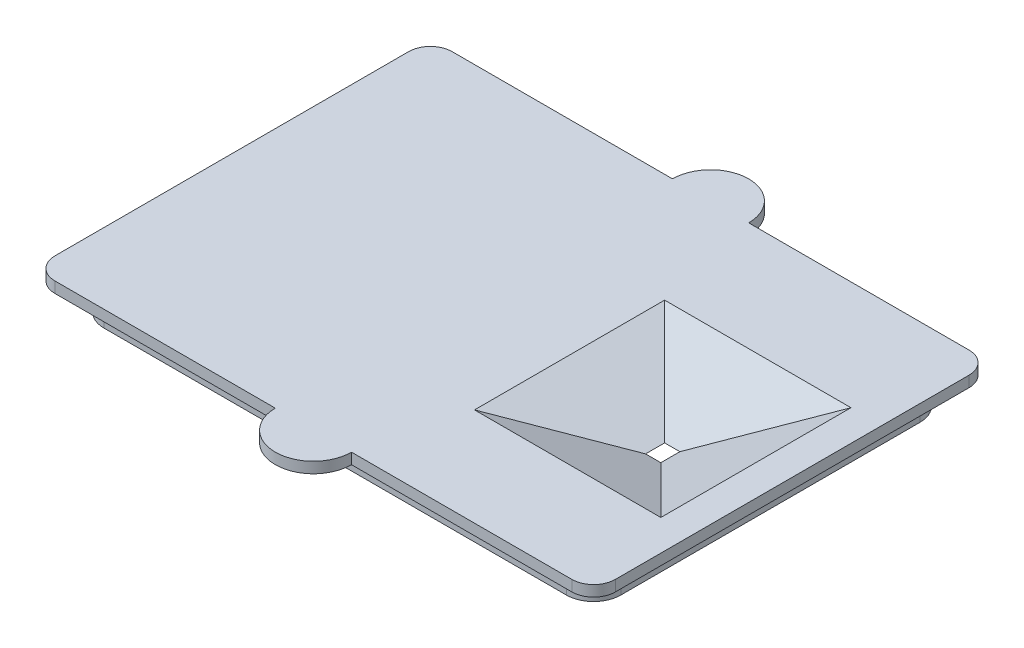
SolidWorks part; units mm, degrees
ref_plane "Front Plane" through (0, 0, 0) normal (0, 0, 1) x (1, 0, 0)
ref_plane "Top Plane" through (0, 0, 0) normal (0, 1, 0) x (1, 0, 0)
ref_plane "Right Plane" through (0, 0, 0) normal (1, 0, 0) x (0, 0, -1)
sketch "Sketch1" plane through (0, 0, 0) normal (0, 1, 0) x (1, 0, 0)
  line L1 (-51.5, -36.5) -> (51.5, -36.5)
  line L2 (-51.5, -36.5) -> (-51.5, 36.5)
  line L3 (-51.5, 36.5) -> (51.5, 36.5)
  line L4 (51.5, -36.5) -> (51.5, 36.5)
  line L5 (-51.5, -36.5) -> (51.5, 36.5) construction
  line L6 (-51.5, 36.5) -> (51.5, -36.5) construction
  point P0 (0, 0)
  dimension "D1" = 103
  dimension "D2" = 73
extrude "Boss-Extrude1" add sketch "Sketch1" along normal blind 2
sketch "Sketch2" plane through (0, 0, 0) normal (0, -1, 0) x (1, 0, 0)
  line L8 (47.5, -32.5) -> (47.5, 32.5)
  line L9 (47.5, 32.5) -> (-47.5, 32.5)
  line L10 (-47.5, 32.5) -> (-47.5, -32.5)
  line L11 (-47.5, -32.5) -> (47.5, -32.5)
  line L12 (47.5, -32.5) -> (47.5, 32.5)
  line L13 (47.5, 32.5) -> (-47.5, 32.5)
  line L14 (-47.5, 32.5) -> (-47.5, -32.5)
  line L15 (-47.5, -32.5) -> (47.5, -32.5)
  dimension "D1" = 4
extrude "Boss-Extrude2" add sketch "Sketch2" along normal blind 5
sketch "Sketch3" plane through (0, 2, 0) normal (0, 1, 0) x (1, 0, 0)
  line L0 (-51.5, -36.5) -> (51.5, -36.5) construction
  line L1 (-7, -36.5) -> (7, -36.5)
  arc A0 (-7, -36.5) -> (7, -36.5) centre (0, -36.5) ccw
  dimension "D1" = 7
extrude "Boss-Extrude3" add sketch "Sketch3" against normal blind 2
sketch "Sketch10" plane through (0, 0, 36.5) normal (0, 0, 1) x (1, 0, 0)
  line L1 (-51.5, 2) -> (51.5, 2)
  line L2 (-51.5, 2) -> (-51.5, 0)
  line L3 (-51.5, 0) -> (51.5, 0)
  line L4 (51.5, 2) -> (51.5, 0)
ref_plane "Plane3" through (0, 0, 0) normal (0, 0, 1) x (1, 0, 0)
mirror "Mirror1" about plane through (0, 0, 0) normal (0, 0, 1) of "Boss-Extrude3"
sketch "Sketch11" plane through (0, 2, 0) normal (0, 1, 0) x (1, 0, 0)
  line L0 (-1.1, 0) -> (1.1, 0) construction
  circle A0 centre (-15.2846, 0) radius 26
  point P4 (-18.7256, 0)
  point P5 (-16.5914, 0)
  point P6 (-14.2478, 0)
  point P7 (-15.2846, 0)
  dimension "D1" = 52
sketch "Sketch12" plane through (0, -5, 0) normal (0, -1, 0) x (1, 0, 0)
  line L0 (10.7023, 32.5) -> (10.7023, -32.5) construction
  line L1 (47.5, 32.5) -> (-47.5, 32.5) construction
  line L2 (-47.5, -32.5) -> (47.5, -32.5) construction
  line L5 (27.3023, -0.7512) -> (30.1023, -0.7512)
  line L6 (27.3023, -0.7512) -> (27.3023, 2.7488)
  line L7 (27.3023, 2.7488) -> (30.1023, 2.7488)
  line L8 (30.1023, -0.7512) -> (30.1023, 2.7488)
  line L9 (27.3023, -0.7512) -> (30.1023, 2.7488) construction
  line L10 (27.3023, 2.7488) -> (30.1023, -0.7512) construction
  point P8 (28.7023, 0.9988)
  dimension "D1" = 2.8
  dimension "D2" = 3.5
  dimension "D3" = 18
extrude "Cut-Extrude3" cut sketch "Sketch12" against normal up to next (7 mm away) draft 66
sketch "Sketch13" plane through (0, -5, 0) normal (0, -1, 0) x (1, 0, 0)
  line L0 (27.3023, 2.7488) -> (27.3023, -0.7512) construction
  line L1 (15.8971, 5.9988) -> (10.5074, 5.9988)
  line L2 (15.8971, 5.9988) -> (15.8971, -4.0012)
  line L3 (15.8971, -4.0012) -> (14.5232, -4.0012)
  line L5 (15.8971, 5.9988) -> (14.5232, -4.0012) construction
  line L6 (15.8971, -4.0012) -> (10.5074, 5.9988) construction
  line L7 (10.5074, 5.9988) -> (-9.1029, 5.9988)
  line L9 (-9.1029, -4.0012) -> (14.5232, -4.0012)
  line L11 (30.1023, 2.7488) -> (27.3023, 2.7488) construction
  line L14 (-9.1029, -13.8104) -> (15.8971, -13.8104)
  line L15 (15.8971, -13.8104) -> (15.8971, -23.8104)
  line L16 (15.8971, -23.8104) -> (-9.1029, -23.8104)
  arc A0 (-9.1029, 5.9988) -> (-9.1029, -23.8104) centre (-9.1029, -8.9058) ccw
  arc A1 (-9.1029, -4.0012) -> (-9.1029, -13.8104) centre (-9.1029, -8.9058) ccw
  point P0 (14.8023, -1.9698)
  point P7 (-9.1029, 0.9988)
  dimension "D1" = 12.5
  dimension "D2" = 10
  dimension "D3" = 5.3897
  dimension "D4" = 25
  dimension "D5" = 3.25
  dimension "D6" = 10
fillet "Fillet4" radius 4 4 edges at (51.5, 1, 36.5) (51.5, 1, -36.5) (-51.5, 1, -36.5) (-51.5, 1, 36.5)
extrude "Cut-Extrude5" cut sketch "Sketch13" against normal blind 5 contours A1 L9 L3 L2 L1 L7 A0 L16 L15 L14
fillet "Fillet5" radius 2 4 edges at (15.8971, 0, -18.8104) (15.8971, -5, -18.8104) (15.8971, -5, 0.9988) (15.8971, 0, 0.9988)
fillet "Fillet6" radius 5 4 edges at (47.5, -2.5, 32.5) (47.5, -2.5, -32.5) (-47.5, -2.5, -32.5) (-47.5, -2.5, 32.5)
